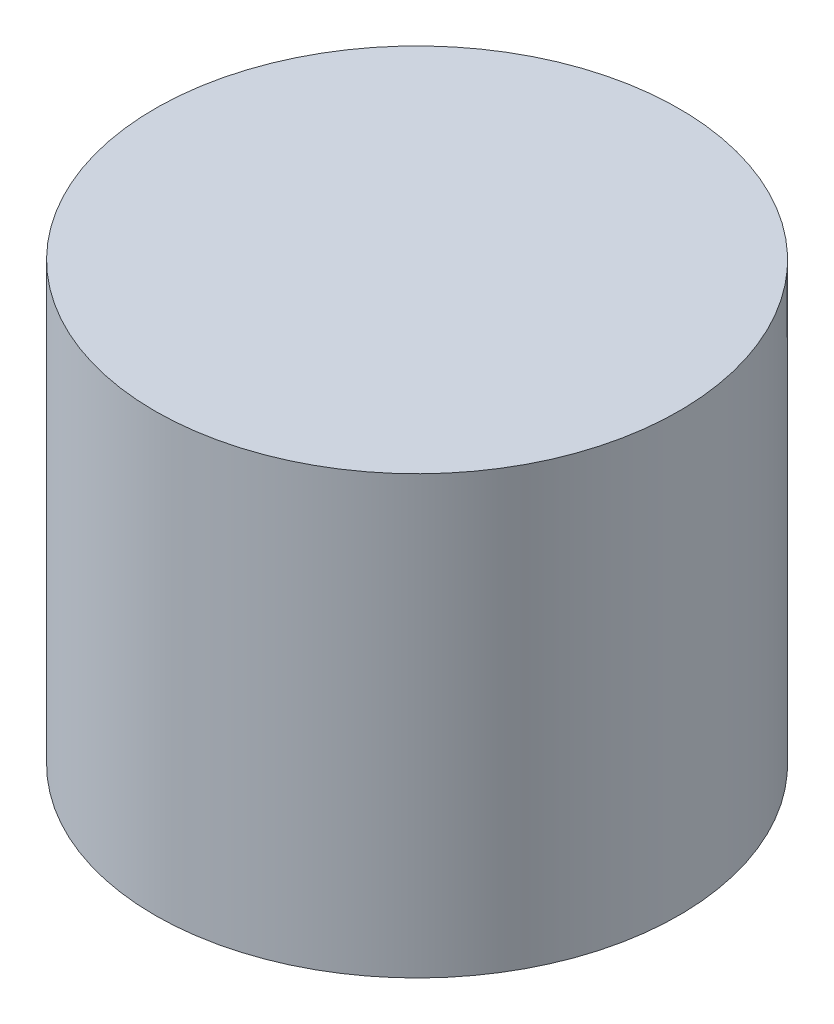
SolidWorks part; units mm, degrees
material "黄铜"
ref_plane "前视基准面" through (0, 0, 0) normal (0, 0, 1) x (1, 0, 0)
ref_plane "上视基准面" through (0, 0, 0) normal (0, 1, 0) x (1, 0, 0)
ref_plane "右视基准面" through (0, 0, 0) normal (1, 0, 0) x (0, 0, -1)
sketch "草图1" plane through (0, 0, 0) normal (0, 1, 0) x (1, 0, 0)
  circle A0 centre (-9.0801, 8.3537) radius 1.5
extrude "凸台-拉伸1" add sketch "草图1" along normal blind 2.5
